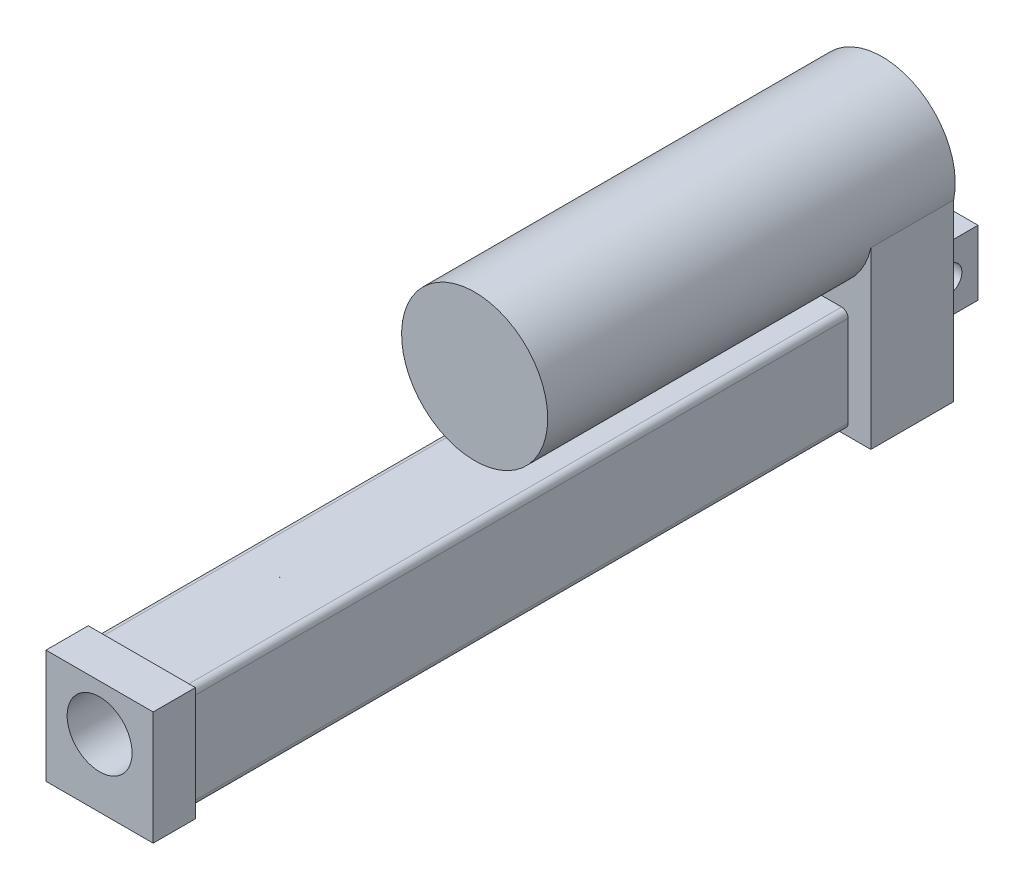
SolidWorks part; units mm, degrees
ref_plane "Front Plane" through (0, 0, 0) normal (0, 0, 1) x (1, 0, 0)
ref_plane "Top Plane" through (0, 0, 0) normal (0, 1, 0) x (1, 0, 0)
ref_plane "Right Plane" through (0, 0, 0) normal (1, 0, 0) x (0, 0, -1)
sketch "Sketch1" plane through (0, 0, 0) normal (0, 0, 1) x (1, 0, 0)
  line L0 (-22, -4.717) -> (-22, -58.5)
  line L3 (-22, -58.5) -> (22, -58.5)
  line L4 (22, -58.5) -> (22, -4.717)
  line L5 (0, 0) -> (0, -58.5) construction
  line L6 (0, 0) -> (0, 22.5) construction
  arc A2 (22, -4.717) -> (-22, -4.717) centre (0, 0) ccw
  dimension "D1" = 22.5
  dimension "D2" = 81
  dimension "D3" = 44
extrude "Boss-Extrude1" add sketch "Sketch1" along normal blind 25.5
sketch "Sketch2" plane through (0, 0, 25.5) normal (0, 0, 1) x (1, 0, 0)
  circle A0 centre (0, 0) radius 22.5
  dimension "D1" = 45
extrude "Boss-Extrude2" add sketch "Sketch2" along normal blind 100
sketch "Sketch3" plane through (0, 0, 25.5) normal (0, 0, 1) x (1, 0, 0)
  line L0 (0, -41) -> (0, -58.5) construction
  line L1 (-15, -57) -> (15, -57)
  line L2 (-15, -57) -> (-15, -25)
  line L3 (-15, -25) -> (15, -25)
  line L4 (15, -57) -> (15, -25)
  line L5 (-15, -57) -> (15, -25) construction
  line L6 (-15, -25) -> (15, -57) construction
  line L7 (-22, -58.5) -> (22, -58.5) construction
  point P0 (0, -41)
  dimension "D1" = 32
  dimension "D2" = 30
  dimension "D3" = 25
extrude "Boss-Extrude3" add sketch "Sketch3" along normal blind 215.5
sketch "Sketch4" plane through (0, 0, 0) normal (0, 0, -1) x (-1, 0, 0)
  line L0 (0, 0) -> (0, -37.7) construction
  line L2 (-9.5, -47.7) -> (9.5, -47.7)
  line L3 (-9.5, -47.7) -> (-9.5, -27.7)
  line L4 (-9.5, -27.7) -> (9.5, -27.7)
  line L5 (9.5, -47.7) -> (9.5, -27.7)
  line L6 (-9.5, -47.7) -> (9.5, -27.7) construction
  line L7 (-9.5, -27.7) -> (9.5, -47.7) construction
  line L8 (-15, -25) -> (15, -25) construction
  circle A0 centre (0, -37.7) radius 10 construction
  dimension "D4" = 20
  dimension "D1" = 19
  dimension "D2" = 20
  dimension "D3" = 2.7
extrude "Boss-Extrude4" add sketch "Sketch4" along normal blind 20
sketch "Sketch5" plane through (9.5, 0, 0) normal (1, 0, 0) x (0, 0, -1)
  line L0 (20, -37.7) -> (11, -37.7) construction
  line L1 (20, -27.7) -> (20, -47.7) construction
  line L2 (11, -37.7) -> (0, -37.7) construction
  line L3 (0, -58.5) -> (0, -4.717) construction
  circle A0 centre (11, -37.7) radius 4.05
  dimension "D2" = 8.1
  dimension "D1" = 11
extrude "Cut-Extrude1" cut sketch "Sketch5" against normal through all
sketch "Sketch6" plane through (0, 0, 241) normal (0, 0, 1) x (1, 0, 0)
  line L0 (0, -37.7) -> (9.5, -37.7) construction
  line L1 (9.5, -27.7) -> (9.5, -47.7) construction
  line L2 (0, 0) -> (0, -37.7) construction
  circle A0 centre (0, -37.7) radius 10
  dimension "D1" = 20
extrude "Boss-Extrude5" add sketch "Sketch6" along normal blind 25
sketch "Sketch7" plane through (0, 0, 241) normal (0, 0, 1) x (1, 0, 0)
  line L8 (16.5, -58.5) -> (16.5, -23.5)
  line L9 (16.5, -23.5) -> (-16.5, -23.5)
  line L10 (-16.5, -23.5) -> (-16.5, -58.5)
  line L11 (-16.5, -58.5) -> (16.5, -58.5)
  line L12 (16.5, -58.5) -> (16.5, -23.5)
  line L13 (16.5, -23.5) -> (-16.5, -23.5)
  line L14 (-16.5, -23.5) -> (-16.5, -58.5)
  line L15 (-16.5, -58.5) -> (16.5, -58.5)
  dimension "D1" = 1.5
extrude "Boss-Extrude6" add sketch "Sketch7" against normal blind 13
sketch "Sketch8" plane through (0, 0, 0) normal (1, 0, 0) x (0, 0, -1)
  line L0 (-266, -37.7) -> (-256, -37.7) construction
  line L1 (-266, -27.7) -> (-266, -47.7) construction
  line L2 (-256, -37.7) -> (-241, -37.7) construction
  line L3 (-241, -58.5) -> (-241, -23.5) construction
  circle A0 centre (-256, -37.7) radius 4.05
  circle A1 centre (11, -37.7) radius 4.05 construction
  dimension "D2" = 267
  dimension "D1" = 15
extrude "Cut-Extrude2" cut sketch "Sketch8" against normal through all both and the other way through all
fillet "Fillet1" radius 2 4 edges at (-15, -57, 126.75) (15, -57, 126.75) (-15, -25, 126.75) (15, -25, 126.75)
sketch "Sketch9" plane through (0, 0, 266) normal (0, 0, 1) x (1, 0, 0)
  circle A1 centre (0, -37.7) radius 10
  circle A2 centre (0, -37.7) radius 10
  dimension "D1" = 0
extrude "Cut-Extrude3" cut sketch "Sketch9" against normal blind 100
